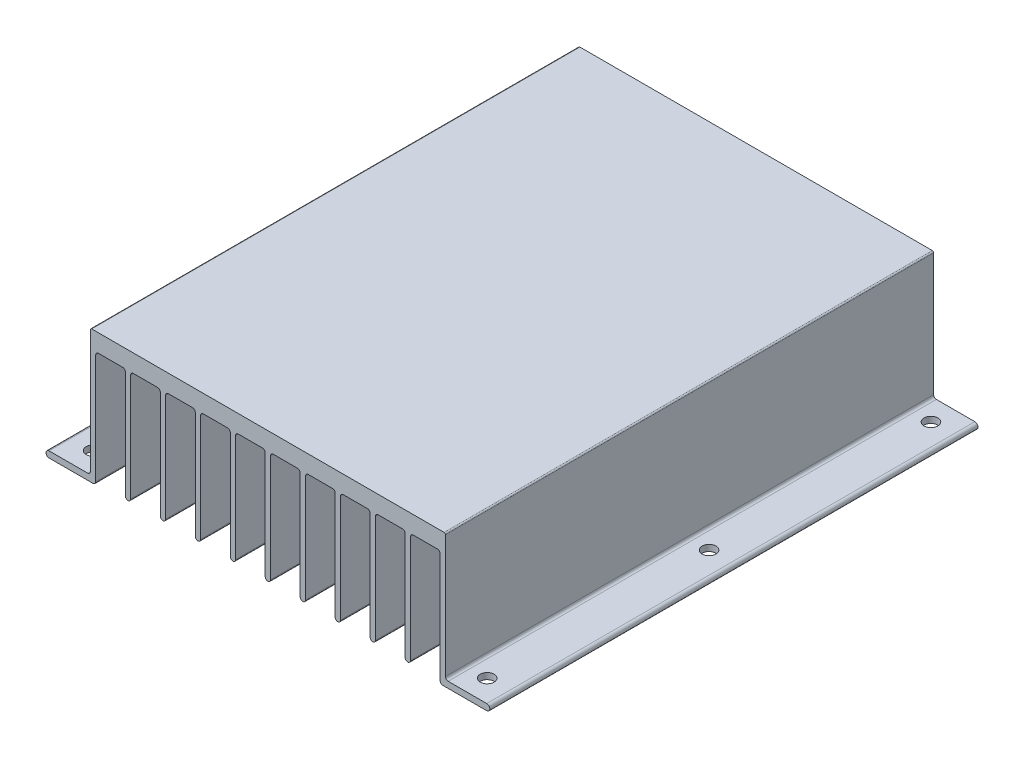
SolidWorks part; units mm, degrees
ref_plane "Front Plane" through (0, 0, 0) normal (0, 0, 1) x (1, 0, 0)
ref_plane "Top Plane" through (0, 0, 0) normal (0, 1, 0) x (1, 0, 0)
ref_plane "Right Plane" through (0, 0, 0) normal (1, 0, 0) x (0, 0, -1)
sketch "Sketch1" plane through (0, 0, 0) normal (0, 0, 1) x (1, 0, 0)
  line L0 (62.6108, -36.322) -> (50.8, -36.322)
  line L1 (50.8, -36.322) -> (50.8, 0)
  line L2 (50.8, 0) -> (-50.8, 0)
  line L3 (-50.8, 0) -> (-50.8, -36.322)
  line L4 (-50.8, -36.322) -> (-62.6108, -36.322)
  line L5 (-62.6108, -38.1005) -> (-49.276, -38.1005)
  line L6 (-49.276, -38.1005) -> (-49.276, -5.0805)
  line L7 (-49.276, -5.0805) -> (-40.7924, -5.0805)
  line L8 (-40.7924, -5.0805) -> (-40.7924, -36.5765)
  line L9 (-39.2684, -36.5765) -> (-39.2684, -5.0805)
  line L10 (-39.2684, -5.0805) -> (-30.7848, -5.0805)
  line L11 (-30.7848, -5.0805) -> (-30.7848, -36.5765)
  line L12 (-29.2608, -36.5765) -> (-29.2608, -5.0805)
  line L13 (-29.2608, -5.0805) -> (-20.7772, -5.0805)
  line L14 (-20.7772, -5.0805) -> (-20.7772, -36.5765)
  line L15 (-19.2532, -36.5765) -> (-19.2532, -5.0805)
  line L16 (-19.2532, -5.0805) -> (-10.7696, -5.0805)
  line L17 (-10.7696, -5.0805) -> (-10.7696, -36.5765)
  line L18 (-9.2456, -36.5765) -> (-9.2456, -5.0805)
  line L19 (-9.2456, -5.0805) -> (-0.762, -5.0805)
  line L20 (-0.762, -5.0805) -> (-0.762, -36.5765)
  line L21 (0.762, -36.5765) -> (0.762, -5.0805)
  line L22 (0.762, -5.0805) -> (9.2456, -5.0805)
  line L23 (9.2456, -5.0805) -> (9.2456, -36.5765)
  line L24 (10.7696, -36.5765) -> (10.7696, -5.0805)
  line L25 (10.7696, -5.0805) -> (19.2532, -5.0805)
  line L26 (19.2532, -5.0805) -> (19.2532, -36.5765)
  line L27 (20.7772, -36.5765) -> (20.7772, -5.0805)
  line L28 (20.7772, -5.0805) -> (29.2608, -5.0805)
  line L29 (29.2608, -5.0805) -> (29.2608, -36.5765)
  line L30 (30.7848, -36.5765) -> (30.7848, -5.0805)
  line L31 (30.7848, -5.0805) -> (39.2684, -5.0805)
  line L32 (39.2684, -5.0805) -> (39.2684, -36.5765)
  line L33 (40.7924, -36.5765) -> (40.7924, -5.0805)
  line L34 (40.7924, -5.0805) -> (49.276, -5.0805)
  line L35 (49.276, -5.0805) -> (49.276, -38.1005)
  line L36 (49.276, -38.1005) -> (62.6108, -38.1005)
  arc A0 (-62.6108, -36.322) -> (-62.6108, -38.1005) centre (-62.6108, -37.2112) ccw
  arc A1 (-40.7924, -36.5765) -> (-39.2684, -36.5765) centre (-40.0304, -36.5765) ccw
  arc A2 (-30.7848, -36.5765) -> (-29.2608, -36.5765) centre (-30.0228, -36.5765) ccw
  arc A3 (-20.7772, -36.5765) -> (-19.2532, -36.5765) centre (-20.0152, -36.5765) ccw
  arc A4 (-10.7696, -36.5765) -> (-9.2456, -36.5765) centre (-10.0076, -36.5765) ccw
  arc A5 (-0.762, -36.5765) -> (0.762, -36.5765) centre (0, -36.5765) ccw
  arc A6 (9.2456, -36.5765) -> (10.7696, -36.5765) centre (10.0076, -36.5765) ccw
  arc A7 (19.2532, -36.5765) -> (20.7772, -36.5765) centre (20.0152, -36.5765) ccw
  arc A8 (29.2608, -36.5765) -> (30.7848, -36.5765) centre (30.0228, -36.5765) ccw
  arc A9 (39.2684, -36.5765) -> (40.7924, -36.5765) centre (40.0304, -36.5765) ccw
  arc A10 (62.6108, -38.1005) -> (62.6108, -36.322) centre (62.6108, -37.2112) ccw
extrude "Boss-Extrude1" add sketch "Sketch1" against normal blind 139.7
hole_wizard "5/32 (0.15625) Diameter Hole1" positions "Sketch3" profile "Sketch2" hole size "5/32" standard "ANSI Inch"
sketch "Sketch3" plane through (0, -38.1005, 0) normal (0, -1, 0) x (-1, 0, 0)
  point P0 (56.388, 6.35)
  point P1 (56.388, 69.85)
  point P2 (56.388, 133.35)
  point P3 (-56.388, 6.35)
  point P4 (-56.388, 69.85)
  point P5 (-56.388, 133.35)
sketch "Sketch2" plane through (-56.388, -38.1005, -6.35) normal (1, 0, 0) x (0, 0, -1)
  line L0 (0, 0) -> (0, 38.1005)
  line L1 (0, 38.1005) -> (1.9844, 38.1005)
  line L2 (1.9844, 38.1005) -> (1.9844, 0)
  line L5 (1.9844, 0) -> (0, 0)
  line L11 (0, -6.35) -> (0, 107.95) construction
  dimension "Thru Hole Dia." = 3.9687
  dimension "Thru Hole Depth" = 38.1005
fillet "Fillet1" radius 0.381 2 edges at (-50.8, 0, -69.85) (50.8, 0, -69.85)
fillet "Fillet2" radius 0.7874 24 edges at (20.7772, -5.0805, -69.85) (-50.8, -36.322, -69.85) (40.7924, -5.0805, -69.85) (-49.276, -5.0805, -69.85) (10.7696, -5.0805, -69.85) (-40.7924, -5.0805, -69.85) (30.7848, -5.0805, -69.85) (-39.2684, -5.0805, -69.85) (49.276, -38.1005, -69.85) (-30.7848, -5.0805, -69.85) (-49.276, -38.1005, -69.85) (-29.2608, -5.0805, -69.85) (19.2532, -5.0805, -69.85) (-20.7772, -5.0805, -69.85) (29.2608, -5.0805, -69.85) (-19.2532, -5.0805, -69.85) (39.2684, -5.0805, -69.85) (-10.7696, -5.0805, -69.85) (49.276, -5.0805, -69.85) (-9.2456, -5.0805, -69.85) (50.8, -36.322, -69.85) (-0.762, -5.0805, -69.85) (0.762, -5.0805, -69.85) (9.2456, -5.0805, -69.85)
sketch "Sketch4" plane through (0, 0, 0) normal (0, 1, 0) x (1, 0, 0)
  line L0 (0, 139.7) -> (0, 0) construction
  line L1 (50.419, 139.7) -> (-50.419, 139.7) construction
  line L2 (0, 69.85) -> (15.902, 69.85) construction
  circle A0 centre (0, 69.85) radius 12.7
  dimension "D1" = 25.4
